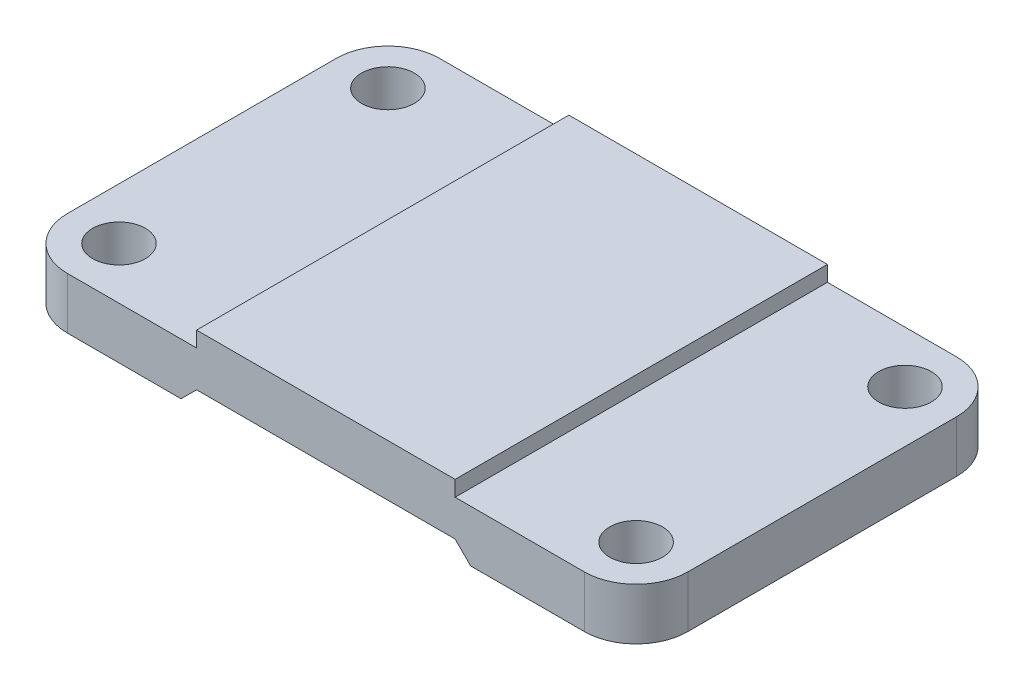
SolidWorks part; units mm, degrees
ref_plane "Front Plane" through (0, 0, 0) normal (0, 0, 1) x (1, 0, 0)
ref_plane "Top Plane" through (0, 0, 0) normal (0, 1, 0) x (1, 0, 0)
ref_plane "Right Plane" through (0, 0, 0) normal (1, 0, 0) x (0, 0, -1)
sketch "Sketch1" plane through (0, 0, 0) normal (0, 1, 0) x (1, 0, 0)
  line L1 (-60, -36) -> (60, -36)
  line L2 (-60, -36) -> (-60, 36)
  line L3 (-60, 36) -> (60, 36)
  line L4 (60, -36) -> (60, 36)
  line L5 (-60, -36) -> (60, 36) construction
  line L6 (-60, 36) -> (60, -36) construction
  point P0 (0, 0)
  dimension "D1" = 120
  dimension "D2" = 72
extrude "Boss-Extrude1" add sketch "Sketch1" along normal blind 10
fillet "Fillet1" radius 10 4 edges at (-60, 5, -36) (60, 5, -36) (60, 5, 36) (-60, 5, 36)
hole_wizard "M12 Tapped Hole1" positions "Sketch2" profile "Sketch3" tap size "M12" standard "DIN" end condition up to next
sketch "Sketch2" plane through (0, 0, 0) normal (0, 1, 0) x (1, 0, 0)
  point P6 (-50, 26)
  point P9 (50, 26)
  point P12 (50, -26)
  point P15 (-50, -26)
sketch "Sketch3" plane through (-50, 0, -26) normal (1, 0, 0) x (0, 0, -1)
  line L0 (0, 0) -> (0, 10)
  line L1 (0, 10) -> (5.1, 10)
  line L2 (5.1, 10) -> (5.1, 0.925)
  line L3 (5.1, 0.925) -> (6.025, 0)
  line L5 (6.025, 0) -> (0, 0)
  line L6 (-5.1, 0.925) -> (-6.025, 0) construction
  line L11 (0, -6.35) -> (0, 107.95) construction
  dimension "Thru Tap Drill Dia." = 10.2
  dimension "Thru Tap Drill Depth" = 10
  dimension "Near C'Sink Dia." = 12.05
  dimension "Near C'Sink Angle" = 90
cosmetic thread "Hole Thread1" parameters "D2"=12
cosmetic thread "Hole Thread2" parameters "D2"=12
cosmetic thread "Hole Thread3" parameters "D2"=12
cosmetic thread "Hole Thread4" parameters "D2"=12
sketch "Sketch4" plane through (0, 0, 0) normal (0, 1, 0) x (1, 0, 0)
  line L0 (50, 36) -> (-50, 36) construction
  line L1 (-25, -36) -> (25, -36)
  line L2 (-25, -36) -> (-25, 36)
  line L3 (-25, 36) -> (25, 36)
  line L4 (25, -36) -> (25, 36)
  line L5 (-25, -36) -> (25, 36) construction
  line L6 (-25, 36) -> (25, -36) construction
  point P0 (0, 0)
  dimension "D1" = 50
extrude "Boss-Extrude2" add sketch "Sketch4" along normal blind 3 from offset 10
sketch "Sketch5" plane through (0, 0, 0) normal (0, 0, 1) x (1, 0, 0)
  line L0 (-28, 0) -> (-25, 3)
  line L1 (-50, 0) -> (50, 0) construction
  line L2 (-25, 3) -> (25, 3)
  line L3 (25, 3) -> (28, 0)
  line L4 (28, 0) -> (-28, 0)
  line L5 (0, 0) -> (0, 13) construction
  line L6 (-25, 13) -> (25, 13) construction
  dimension "D1" = 56
  dimension "D2" = 3
extrude "Cut-Extrude1" cut sketch "Sketch5" against normal through all both and the other way through all
